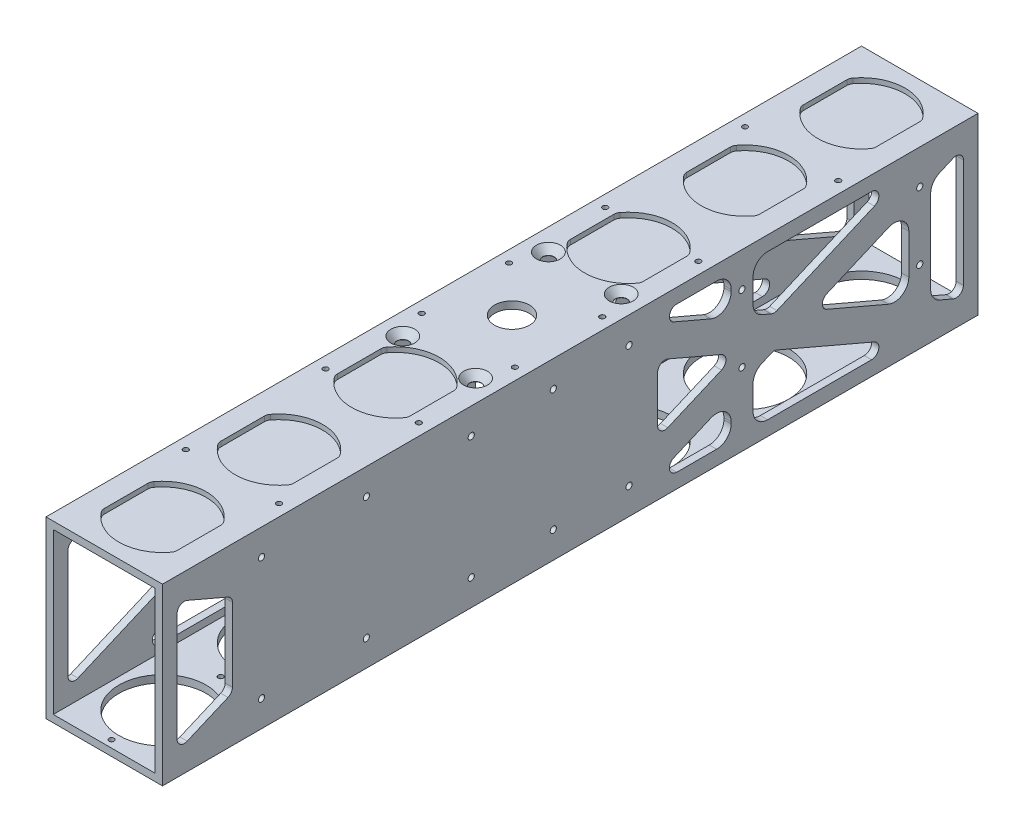
SolidWorks part; units mm, degrees
material "6061-T6 (SS)"
ref_plane "Front Plane" through (0, 0, 0) normal (0, 0, 1) x (1, 0, 0)
ref_plane "Top Plane" through (0, 0, 0) normal (0, 1, 0) x (1, 0, 0)
ref_plane "Right Plane" through (0, 0, 0) normal (1, 0, 0) x (0, 0, -1)
sketch "Sketch1" plane through (0, 0, 0) normal (0, 0, 1) x (1, 0, 0)
  line L0 (3.175, 3.175) -> (3.175, 73.025)
  line L1 (0, 0) -> (50.8, 0)
  line L2 (0, 0) -> (0, 76.2)
  line L3 (0, 76.2) -> (50.8, 76.2)
  line L4 (50.8, 0) -> (50.8, 76.2)
  line L5 (3.175, 73.025) -> (47.625, 73.025)
  line L6 (47.625, 3.175) -> (47.625, 73.025)
  line L7 (3.175, 3.175) -> (47.625, 3.175)
  dimension "D1" = 76.2
  dimension "D2" = 50.8
  dimension "D3" = 3.175
extrude "Boss-Extrude1" add sketch "Sketch1" along normal blind 355.6
sketch "Sketch2" plane through (50.8, 0, 0) normal (1, 0, 0) x (0, 0, -1)
  line L0 (-355.6, 76.2) -> (-177.8, 0) construction
  line L1 (-355.6, 0) -> (0, 0) construction
  line L2 (-177.8, 0) -> (-177.8, 76.2) construction
  line L3 (-355.6, 76.2) -> (0, 76.2) construction
  line L4 (-177.8, 76.2) -> (0, 0) construction
  line L5 (-355.6, 0) -> (-177.8, 76.2) construction
  line L6 (0, 76.2) -> (-177.8, 0) construction
  line L7 (-171.45, 61.755) -> (-171.45, 14.445)
  line L8 (-310.4456, 63.7567) -> (-267.9507, 45.5446)
  line L9 (-358.1014, 70.3634) -> (-180.3014, -5.8366) construction
  line L10 (-353.0986, 82.0366) -> (-175.2986, 5.8366) construction
  line L11 (-344.8243, 64.6733) -> (-289.6294, 41.0183)
  line L12 (-358.1014, 5.8366) -> (-180.3014, 82.0366) construction
  line L13 (-175.2986, 82.0366) -> (2.5014, 5.8366) construction
  line L14 (-353.0986, -5.8366) -> (-175.2986, 70.3634) construction
  line L15 (-184.15, 61.755) -> (-184.15, 14.445)
  line L16 (-45.1544, 63.7567) -> (-87.6493, 45.5446)
  line L17 (-10.7757, 64.6733) -> (-65.9706, 41.0183)
  line L18 (-132.6456, 63.7567) -> (-90.1507, 45.5446)
  line L19 (-167.0243, 64.6733) -> (-111.8294, 41.0183)
  line L20 (-6.35, 6.35) -> (-6.35, 69.85)
  line L21 (-6.35, 69.85) -> (-349.25, 69.85)
  line L22 (-349.25, 69.85) -> (-349.25, 6.35)
  line L23 (-349.25, 6.35) -> (-6.35, 6.35)
  line L24 (-6.35, 14.445) -> (-6.35, 61.755)
  line L25 (-224.2051, 69.85) -> (-309.1949, 69.85)
  line L26 (-349.25, 61.755) -> (-349.25, 14.445)
  line L27 (-309.1949, 6.35) -> (-224.2051, 6.35)
  line L28 (-344.8243, 11.5267) -> (-289.6294, 35.1817)
  line L29 (-310.4456, 12.4433) -> (-267.9507, 30.6554)
  line L30 (-265.4493, 45.5446) -> (-222.9544, 63.7567)
  line L31 (-243.7706, 41.0183) -> (-188.5757, 64.6733)
  line L32 (-180.3014, 70.3634) -> (-2.5014, -5.8366) construction
  line L33 (-265.4493, 30.6554) -> (-222.9544, 12.4433)
  line L34 (2.5014, 70.3634) -> (-175.2986, -5.8366) construction
  line L35 (-2.5014, 82.0366) -> (-180.3014, 5.8366) construction
  line L36 (-243.7706, 35.1817) -> (-188.5757, 11.5267)
  line L37 (-111.8294, 35.1817) -> (-167.0243, 11.5267)
  line L38 (-87.6493, 30.6554) -> (-45.1544, 12.4433)
  line L39 (-65.9706, 35.1817) -> (-10.7757, 11.5267)
  line L40 (-90.1507, 30.6554) -> (-132.6456, 12.4433)
  line L41 (-131.3949, 69.85) -> (-46.4051, 69.85)
  line L42 (-131.3949, 6.35) -> (-46.4051, 6.35)
  arc A0 (-65.9706, 35.1817) -> (-65.9706, 41.0183) centre (-64.7199, 38.1) cw
  arc A1 (-87.6493, 45.5446) -> (-90.1507, 45.5446) centre (-88.9, 48.4629) cw
  arc A2 (-167.0243, 11.5267) -> (-171.45, 14.445) centre (-168.275, 14.445) cw
  arc A3 (-171.45, 61.755) -> (-167.0243, 64.6733) centre (-168.275, 61.755) cw
  arc A4 (-224.2051, 6.35) -> (-222.9544, 12.4433) centre (-224.2051, 9.525) ccw
  arc A5 (-309.1949, 6.35) -> (-310.4456, 12.4433) centre (-309.1949, 9.525) cw
  arc A6 (-265.4493, 30.6554) -> (-267.9507, 30.6554) centre (-266.7, 27.7371) ccw
  arc A7 (-188.5757, 11.5267) -> (-184.15, 14.445) centre (-187.325, 14.445) ccw
  arc A8 (-184.15, 61.755) -> (-188.5757, 64.6733) centre (-187.325, 61.755) ccw
  arc A9 (-243.7706, 35.1817) -> (-243.7706, 41.0183) centre (-242.5199, 38.1) cw
  arc A10 (-222.9544, 63.7567) -> (-224.2051, 69.85) centre (-224.2051, 66.675) ccw
  arc A11 (-309.1949, 69.85) -> (-310.4456, 63.7567) centre (-309.1949, 66.675) ccw
  arc A12 (-265.4493, 45.5446) -> (-267.9507, 45.5446) centre (-266.7, 48.4629) cw
  arc A13 (-289.6294, 35.1817) -> (-289.6294, 41.0183) centre (-290.8801, 38.1) ccw
  arc A14 (-344.8243, 11.5267) -> (-349.25, 14.445) centre (-346.075, 14.445) cw
  arc A15 (-349.25, 61.755) -> (-344.8243, 64.6733) centre (-346.075, 61.755) cw
  arc A16 (-111.8294, 35.1817) -> (-111.8294, 41.0183) centre (-113.0801, 38.1) ccw
  arc A17 (-6.35, 61.755) -> (-10.7757, 64.6733) centre (-9.525, 61.755) ccw
  arc A18 (-6.35, 14.445) -> (-10.7757, 11.5267) centre (-9.525, 14.445) cw
  arc A19 (-45.1544, 12.4433) -> (-46.4051, 6.35) centre (-46.4051, 9.525) cw
  arc A20 (-131.3949, 6.35) -> (-132.6456, 12.4433) centre (-131.3949, 9.525) cw
  arc A21 (-87.6493, 30.6554) -> (-90.1507, 30.6554) centre (-88.9, 27.7371) ccw
  arc A22 (-45.1544, 63.7567) -> (-46.4051, 69.85) centre (-46.4051, 66.675) ccw
  arc A23 (-131.3949, 69.85) -> (-132.6456, 63.7567) centre (-131.3949, 66.675) ccw
  point P36 (-260.35, 0)
  point P37 (-260.35, 101.6)
  point P38 (-247.65, 0)
  point P39 (-247.65, 101.6)
  point P77 (-266.7, 31.1914)
  point P83 (-250.5799, 38.1)
  point P104 (-30.9367, 6.35)
  point P107 (-146.8633, 6.35)
  point P110 (-88.9, 31.1914)
  point P113 (-30.9367, 69.85)
  point P116 (-146.8633, 69.85)
  dimension "D13" = 3.175
  dimension "D14" = 3.175
  dimension "D11" = 6.35
  dimension "D12" = 6.35
  dimension "D2" = 6.35
  dimension "D3" = 6.35
  dimension "D4" = 6.35
  dimension "D5" = 6.35
  dimension "D6" = 6.35
  dimension "D7" = 6.35
  dimension "D8" = 6.35
  dimension "D9" = 6.35
  dimension "D10" = 6.35
extrude "Cut-Extrude2" cut sketch "Sketch2" against normal through all
hole_wizard "9/16 (0.5625) Diameter Hole1" positions "Sketch4" profile "Sketch5" hole size "9/16" standard "Ansi Inch"
sketch "Sketch4" plane through (0, 76.2, 0) normal (0, 1, 0) x (-1, 0, 0)
  line L4 (-50.8, 355.6) -> (-50.8, 0) construction
  line L5 (-50.8, 177.8) -> (0, 177.8) construction
  line L6 (0, 355.6) -> (0, 0) construction
  point P0 (-25.4, 177.8)
sketch "Sketch5" plane through (25.4, 76.2, 177.8) normal (1, 0, 0) x (0, 0, 1)
  line L0 (0, 0) -> (0, 3.175)
  line L1 (0, 3.175) -> (7.62, 3.175)
  line L2 (7.62, 3.175) -> (7.62, 0)
  line L5 (7.62, 0) -> (0, 0)
  line L11 (0, -6.35) -> (0, 107.95) construction
  dimension "Thru Hole Dia." = 15.24
  dimension "Thru Hole Depth" = 3.175
sketch "Sketch6" plane through (0, 76.2, 0) normal (0, 1, 0) x (1, 0, 0)
  line L0 (50.8, 0) -> (0, 0) construction
  line L2 (50.8, -355.6) -> (50.8, 0) construction
  circle A0 centre (25.4, -25.4) radius 19.05
  circle A1 centre (25.4, -76.2) radius 19.05
  circle A2 centre (25.4, -127) radius 19.05
  circle A3 centre (25.4, -177.8) radius 19.05 [skipped]
  circle A4 centre (25.4, -228.6) radius 19.05
  circle A5 centre (25.4, -279.4) radius 19.05
  circle A6 centre (25.4, -330.2) radius 19.05
  dimension "D1" = 38.1
  dimension "D2" = 25.4
  dimension "D3" = 25.4
  dimension "D5" = 7
extrude "Cut-Extrude3" cut sketch "Sketch6" against normal through all
hole_wizard "CSK for #10 Flat Head Socket Cap Screw1" positions "Sketch8" profile "Sketch7" countersink size "#10" standard "Ansi Inch" end condition up to next
sketch "Sketch8" plane through (0, 76.2, 0) normal (0, 1, 0) x (-1, 0, 0)
  line L0 (-50.8, 177.8) -> (0, 177.8) construction
  line L1 (-50.8, 355.6) -> (-50.8, 0) construction
  line L2 (0, 355.6) -> (0, 0) construction
  line L4 (-25.4, 0) -> (-25.4, 355.6) construction
  line L5 (-50.8, 0) -> (0, 0) construction
  line L6 (-50.8, 355.6) -> (0, 355.6) construction
  point P0 (-41.275, 146.05)
  point P1 (-9.525, 146.05)
  point P3 (-41.275, 209.55)
  point P5 (-9.525, 209.55)
  dimension "D1" = 31.75
  dimension "D2" = 15.875
  dimension "D3" = 15.875
  dimension "D4" = 31.75
sketch "Sketch7" plane through (41.275, 76.2, 146.05) normal (1, 0, 0) x (0, 0, 1)
  line L0 (0, 0) -> (0, 3.175)
  line L1 (0, 3.175) -> (2.5527, 3.175)
  line L2 (2.5527, 3.175) -> (2.5527, 3.068)
  line L3 (2.5527, 3.068) -> (5.2197, 0)
  line L5 (5.2197, 0) -> (0, 0)
  line L6 (-2.5527, 3.068) -> (-5.2197, 0) construction
  line L11 (0, -6.35) -> (0, 107.95) construction
  dimension "Thru Hole Dia." = 5.1054
  dimension "Thru Hole Depth" = 3.175
  dimension "Near C'Sink Dia." = 10.4394
  dimension "Near C'Sink Angle" = 82
sketch "Sketch9" plane through (0, 0, 0) normal (0, -1, 0) x (1, 0, 0)
  line L0 (0, 355.6) -> (0, 0) construction
  circle A0 centre (25.4, 177.8) radius 19.05
  circle A1 centre (25.4, 127) radius 19.05 construction
  dimension "D1" = 38.1
  dimension "D2" = 25.4
  dimension "D3" = 50.8
extrude "Cut-Extrude4" cut sketch "Sketch9" against normal up to next
sketch "Sketch10" plane through (50.8, 0, 0) normal (1, 0, 0) x (0, 0, -1)
  line L0 (-266.7, 64.77) -> (-266.7, 11.43) construction
  line L1 (-312.42, 64.77) -> (-220.98, 64.77) construction
  line L2 (-312.42, 64.77) -> (-312.42, 11.43) construction
  line L3 (-312.42, 11.43) -> (-220.98, 11.43) construction
  line L4 (-220.98, 64.77) -> (-220.98, 11.43) construction
  line L5 (-355.6, 38.1) -> (0, 38.1) construction
  line L6 (-355.6, 0) -> (-355.6, 76.2) construction
  line L7 (0, 0) -> (0, 76.2) construction
  line L9 (-325.12, 7.62) -> (-208.28, 7.62) construction
  line L10 (-325.12, 19.9715) -> (-325.12, 56.2285) construction
  line L11 (-325.12, 68.58) -> (-208.28, 68.58) construction
  line L12 (-171.45, 4.1872) -> (-171.45, 9.63) construction
  line L13 (-325.12, 7.62) -> (-208.28, 68.58) construction
  line L14 (-325.12, 68.58) -> (-208.28, 7.62) construction
  line L15 (-325.12, 56.2285) -> (-325.12, 19.9715)
  line L18 (-171.45, 9.63) -> (-171.45, 4.1872)
  line L20 (-188.5757, 64.6733) -> (-243.7706, 41.0183) construction
  line L22 (-243.7706, 35.1817) -> (-188.5757, 11.5267) construction
  line L24 (-167.0243, 73.9096) -> (-243.7706, 41.0183)
  line L25 (-243.7706, 35.1817) -> (-171.45, 4.1872)
  line L26 (-289.6294, 41.0183) -> (-344.8243, 64.6733) construction
  line L27 (-344.8243, 11.5267) -> (-289.6294, 35.1817) construction
  line L28 (-289.6294, 41.0183) -> (-325.12, 56.2285)
  line L29 (-325.12, 19.9715) -> (-289.6294, 35.1817)
  line L30 (-355.6, 76.2) -> (0, 76.2) construction
  line L31 (-310.4456, 63.7567) -> (-267.9507, 45.5446) construction
  line L32 (-224.2051, 69.85) -> (-309.1949, 69.85) construction
  line L33 (-265.4493, 45.5446) -> (-222.9544, 63.7567) construction
  line L34 (-222.9544, 12.4433) -> (-265.4493, 30.6554) construction
  line L35 (-267.9507, 30.6554) -> (-310.4456, 12.4433) construction
  line L36 (-309.1949, 6.35) -> (-224.2051, 6.35) construction
  line L37 (-310.4456, 63.7567) -> (-267.9507, 45.5446)
  line L38 (-224.2051, 69.85) -> (-309.1949, 69.85)
  line L39 (-265.4493, 45.5446) -> (-222.9544, 63.7567)
  line L40 (-222.9544, 12.4433) -> (-265.4493, 30.6554)
  line L41 (-267.9507, 30.6554) -> (-310.4456, 12.4433)
  line L42 (-309.1949, 6.35) -> (-224.2051, 6.35)
  line L45 (-139.7, 52.9628) -> (-139.7, 23.2372)
  line L46 (-111.8294, 41.0183) -> (-167.0243, 64.6733) construction
  line L47 (-167.0243, 11.5267) -> (-111.8294, 35.1817) construction
  line L48 (-171.45, 61.755) -> (-171.45, 14.445) construction
  line L49 (-139.7, 52.9628) -> (-167.0243, 64.6733)
  line L50 (-171.45, 9.63) -> (-139.7, 23.2372)
  line L51 (-167.0243, 64.6733) -> (-167.0243, 73.9096)
  arc A0 (-243.7706, 41.0183) -> (-243.7706, 35.1817) centre (-242.5199, 38.1) ccw construction
  arc A2 (-243.7706, 41.0183) -> (-243.7706, 35.1817) centre (-242.5199, 38.1) ccw
  arc A4 (-289.6294, 35.1817) -> (-289.6294, 41.0183) centre (-290.8801, 38.1) ccw construction
  arc A5 (-289.6294, 35.1817) -> (-289.6294, 41.0183) centre (-290.8801, 38.1) ccw
  arc A6 (-309.1949, 69.85) -> (-310.4456, 63.7567) centre (-309.1949, 66.675) ccw construction
  arc A7 (-222.9544, 63.7567) -> (-224.2051, 69.85) centre (-224.2051, 66.675) ccw construction
  arc A8 (-267.9507, 45.5446) -> (-265.4493, 45.5446) centre (-266.7, 48.4629) ccw construction
  arc A9 (-265.4493, 30.6554) -> (-267.9507, 30.6554) centre (-266.7, 27.7371) ccw construction
  arc A10 (-310.4456, 12.4433) -> (-309.1949, 6.35) centre (-309.1949, 9.525) ccw construction
  arc A11 (-224.2051, 6.35) -> (-222.9544, 12.4433) centre (-224.2051, 9.525) ccw construction
  arc A12 (-309.1949, 69.85) -> (-310.4456, 63.7567) centre (-309.1949, 66.675) ccw
  arc A13 (-222.9544, 63.7567) -> (-224.2051, 69.85) centre (-224.2051, 66.675) ccw
  arc A14 (-267.9507, 45.5446) -> (-265.4493, 45.5446) centre (-266.7, 48.4629) ccw
  arc A15 (-265.4493, 30.6554) -> (-267.9507, 30.6554) centre (-266.7, 27.7371) ccw
  arc A16 (-310.4456, 12.4433) -> (-309.1949, 6.35) centre (-309.1949, 9.525) ccw
  arc A17 (-224.2051, 6.35) -> (-222.9544, 12.4433) centre (-224.2051, 9.525) ccw
  point P13 (-266.7, 38.1)
  dimension "D1" = 53.34
  dimension "D2" = 215.9
  dimension "D3" = 116.84
  dimension "D4" = 60.96
  dimension "D5" = 91.44
  dimension "D7" = 30.48
  dimension "D8" = 7.62
  dimension "D9" = 3.81
  dimension "D10" = 12.7
extrude "Boss-Extrude2" add sketch "Sketch10" against normal up to surface (3.175 mm away) up to face at (47.625, 16.3557, 88.9)
fillet "Fillet1" radius 3.175 4 edges at (49.2125, 19.9715, 325.12) (49.2125, 56.2285, 325.12) (49.2125, 23.2372, 139.7) (49.2125, 52.9628, 139.7)
hole_wizard "#6-32 Tapped Hole1" positions "Sketch12" profile "Sketch11" tap size "#6-32" standard "Ansi Inch"
sketch "Sketch12" plane through (50.8, 0, 0) normal (1, 0, 0) x (0, 0, -1)
  point P0 (-312.42, 64.77)
  point P1 (-266.7, 64.77)
  point P4 (-220.98, 64.77)
  point P7 (-220.98, 11.43)
  point P10 (-266.7, 11.43)
  point P13 (-312.42, 11.43)
sketch "Sketch11" plane through (50.8, 64.77, 312.42) normal (0, 1, 0) x (0, 0, -1)
  line L0 (0, 0) -> (0, 3.175)
  line L1 (0, 3.175) -> (1.3525, 3.175)
  line L2 (1.3525, 3.175) -> (1.3525, 0)
  line L5 (1.3525, 0) -> (0, 0)
  line L11 (0, -6.35) -> (0, 107.95) construction
  dimension "Thru Tap Drill Dia." = 2.7051
  dimension "Thru Tap Drill Depth" = 3.175
cosmetic thread "Hole Thread1"
cosmetic thread "Hole Thread2"
cosmetic thread "Hole Thread3"
cosmetic thread "Hole Thread4"
cosmetic thread "Hole Thread5"
cosmetic thread "Hole Thread6"
sketch "Sketch13" plane through (50.8, 0, 0) normal (1, 0, 0) x (0, 0, -1)
  line L0 (-355.6, 38.1) -> (0, 38.1) construction
  line L1 (-355.6, 0) -> (-355.6, 76.2) construction
  line L2 (0, 0) -> (0, 76.2) construction
  line L4 (-197.6628, 8.1026) -> (-139.7, 8.1026) construction
  line L5 (-197.6628, 8.1026) -> (-197.6628, 68.0974) construction
  line L6 (-197.6628, 68.0974) -> (-139.7, 68.0974) construction
  line L7 (-139.7, 8.1026) -> (-139.7, 68.0974) construction
  line L8 (-197.6628, 8.1026) -> (-139.7, 68.0974) construction
  line L9 (-197.6628, 68.0974) -> (-139.7, 8.1026) construction
  line L10 (-185.1914, 11.5697) -> (-152.1714, 11.5697) construction
  line L11 (-185.1914, 11.5697) -> (-185.1914, 64.6303) construction
  line L12 (-185.1914, 64.6303) -> (-152.1714, 64.6303) construction
  line L13 (-152.1714, 11.5697) -> (-152.1714, 64.6303) construction
  line L14 (-185.1914, 11.5697) -> (-152.1714, 64.6303) construction
  line L15 (-185.1914, 64.6303) -> (-152.1714, 11.5697) construction
  point P6 (-168.6814, 38.1)
  point P11 (-168.6814, 38.1)
  dimension "D1" = 139.7
  dimension "D2" = 59.9948
  dimension "D3" = 57.9628
  dimension "D4" = 53.0606
  dimension "D5" = 33.02
hole_wizard "#6-32 Tapped Hole2" positions "Sketch15" profile "Sketch14" tap size "#6-32" standard "Ansi Inch"
sketch "Sketch15" plane through (50.8, 0, 0) normal (1, 0, 0) x (0, 0, -1)
  point P0 (-152.1714, 64.6303)
  point P1 (-185.1914, 64.6303)
  point P4 (-185.1914, 11.5697)
  point P7 (-152.1714, 11.5697)
cosmetic thread "Hole Thread7"
cosmetic thread "Hole Thread8"
cosmetic thread "Hole Thread9"
cosmetic thread "Hole Thread10"
sketch "Sketch14" plane through (50.8, 64.6303, 152.1714) normal (0, 1, 0) x (0, 0, -1)
  line L0 (0, 0) -> (0, 3.175)
  line L1 (0, 3.175) -> (1.3525, 3.175)
  line L2 (1.3525, 3.175) -> (1.3525, 0)
  line L5 (1.3525, 0) -> (0, 0)
  line L11 (0, -6.35) -> (0, 107.95) construction
  dimension "Thru Tap Drill Dia." = 2.7051
  dimension "Thru Tap Drill Depth" = 3.175
sketch "Sketch20" plane through (50.8, 0, 0) normal (1, 0, 0) x (0, 0, -1)
  line L0 (-102.87, 76.2) -> (-102.87, 0) construction
  line L1 (-355.6, 76.2) -> (0, 76.2) construction
  line L2 (-355.6, 0) -> (0, 0) construction
  line L3 (-25.4, 76.2) -> (-25.4, 0) construction
  line L4 (0, 0) -> (0, 76.2) construction
  line L5 (-107.6325, 69.85) -> (-107.6325, 53.0368)
  line L6 (-30.1625, 56.3646) -> (-30.1625, 19.8354)
  line L7 (-98.1075, 69.85) -> (-98.1075, 48.9547)
  line L8 (-20.6375, 60.4468) -> (-20.6375, 15.7532)
  line L9 (-46.4051, 69.85) -> (-131.3949, 69.85) construction
  line L10 (-132.6456, 63.7567) -> (-90.1507, 45.5446) construction
  line L11 (-90.1507, 30.6554) -> (-132.6456, 12.4433) construction
  line L12 (-131.3949, 6.35) -> (-46.4051, 6.35) construction
  line L13 (-10.7757, 64.6733) -> (-65.9706, 41.0183) construction
  line L14 (-65.9706, 35.1817) -> (-10.7757, 11.5267) construction
  line L15 (-98.1075, 69.85) -> (-107.6325, 69.85)
  line L16 (-107.6325, 53.0368) -> (-98.1075, 48.9547)
  line L17 (-98.1075, 27.2453) -> (-107.6325, 23.1632)
  line L18 (-107.6325, 6.35) -> (-98.1075, 6.35)
  line L19 (-20.6375, 60.4468) -> (-30.1625, 56.3646)
  line L20 (-30.1625, 19.8354) -> (-20.6375, 15.7532)
  line L21 (-98.1075, 76.2) -> (-98.1075, 0) construction
  line L22 (-107.6325, 76.2) -> (-107.6325, 0) construction
  line L23 (-107.6325, 23.1632) -> (-107.6325, 6.35)
  line L24 (-98.1075, 27.2453) -> (-98.1075, 6.35)
  line L25 (-30.1625, 76.2) -> (-30.1625, 0) construction
  line L26 (-20.6375, 76.2) -> (-20.6375, 0) construction
  dimension "D1" = 77.47
  dimension "D2" = 25.4
  dimension "D3" = 4.7625
  dimension "D4" = 4.7625
extrude "Boss-Extrude7" add sketch "Sketch20" against normal up to surface (3.175 mm away) up to face at (47.625, 64.6303, 153.5239)
fillet "Fillet6" radius 6.35 12 edges at (49.2125, 60.4468, 20.6375) (49.2125, 15.7532, 20.6375) (49.2125, 19.8354, 30.1625) (49.2125, 56.3646, 30.1625) (49.2125, 6.35, 98.1075) (49.2125, 6.35, 107.6325) (49.2125, 23.1632, 107.6325) (49.2125, 27.2453, 98.1075) (49.2125, 69.85, 98.1075) (49.2125, 48.9547, 98.1075) (49.2125, 69.85, 107.6325) (49.2125, 53.0368, 107.6325)
hole_wizard "#6-32 Tapped Hole3" positions "Sketch24" profile "Sketch23" tap size "#6-32" standard "Ansi Inch"
sketch "Sketch24" plane through (50.8, 0, 0) normal (1, 0, 0) x (0, 0, -1)
  line L0 (0, 38.1) -> (-164.5823, 38.1) construction
  line L1 (0, 0) -> (0, 76.2) construction
  point P0 (-102.9, 61.1)
  point P1 (-25.4, 61.1)
  point P3 (-25.4, 31.75)
  point P5 (-102.9, 31.75)
  dimension "D1" = 77.5
  dimension "D2" = 6.35
  dimension "D3" = 29.35
  dimension "D4" = 25.4
sketch "Sketch23" plane through (50.8, 61.1, 102.9) normal (0, 1, 0) x (0, 0, -1)
  line L0 (0, 0) -> (0, 10.2107)
  line L1 (0, 10.2107) -> (1.3525, 9.398)
  line L2 (1.3525, 9.398) -> (1.3525, 0)
  line L5 (1.3525, 0) -> (0, 0)
  line L10 (0, 10.2107) -> (-1.3525, 9.398) construction
  line L11 (0, -6.35) -> (0, 107.95) construction
  dimension "Tap Drill Dia." = 2.7051
  dimension "Tap Drill Depth" = 9.398
  dimension "Drill Angle" = 118
cosmetic thread "Hole Thread11"
cosmetic thread "Hole Thread12"
cosmetic thread "Hole Thread13"
cosmetic thread "Hole Thread14"
hole_wizard "#4-40 Tapped Hole1" positions "Sketch26" profile "Sketch27" tap size "#4-40" standard "Ansi Inch"
sketch "Sketch26" plane through (0, 0, 0) normal (0, -1, 0) x (1, 0, 0)
  line L0 (0, 355.6) -> (50.8, 355.6) construction
  line L1 (25.4, 311.15) -> (25.4, 298.45) construction
  line L3 (0, 0) -> (50.8, 0) construction
  circle A0 centre (25.4, 330.2) radius 19.05 construction
  circle A1 centre (25.4, 279.4) radius 19.05 construction
  point P0 (25.4, 304.8)
  point P1 (25.4, 352.425)
  point P26 (25.4, 254)
  point P27 (25.4, 203.2)
  point P28 (25.4, 152.4)
  point P29 (25.4, 101.6)
  point P30 (25.4, 50.8)
  point P31 (25.4, 3.175)
  dimension "D1" = 3.175
  dimension "D3" = 3.175
  dimension "D4" = 50.8
  dimension "D2" = 6
sketch "Sketch27" plane through (25.4, 0, 304.8) normal (1, 0, 0) x (0, 0, -1)
  line L0 (0, 0) -> (0, 3.175)
  line L1 (0, 3.175) -> (1.1303, 3.175)
  line L2 (1.1303, 3.175) -> (1.1303, 0)
  line L5 (1.1303, 0) -> (0, 0)
  line L11 (0, -6.35) -> (0, 107.95) construction
  dimension "Thread Major Dia." = 2.2606
  dimension "Thru Tap Drill Depth" = 3.175
sketch "Sketch29" plane through (0, 76.2, 0) normal (0, 1, 0) x (1, 0, 0)
  line L0 (9.525, -14.8697) -> (9.525, -35.9303)
  line L3 (41.275, -14.8697) -> (41.275, -35.9303)
  line L5 (0, -355.6) -> (0, 0) construction
  line L6 (50.8, -355.6) -> (50.8, 0) construction
  line L7 (41.275, -116.4697) -> (41.275, -137.5303)
  line L8 (9.525, -116.4697) -> (9.525, -137.5303)
  line L9 (41.275, -65.6697) -> (41.275, -86.7303)
  line L10 (9.525, -65.6697) -> (9.525, -86.7303)
  line L11 (41.275, -218.0697) -> (41.275, -239.1303)
  line L12 (9.525, -218.0697) -> (9.525, -239.1303)
  line L13 (41.275, -268.8697) -> (41.275, -289.9303)
  line L14 (9.525, -268.8697) -> (9.525, -289.9303)
  line L15 (41.275, -319.6697) -> (41.275, -340.7303)
  line L16 (9.525, -319.6697) -> (9.525, -340.7303)
  circle A0 centre (25.4, -25.4) radius 19.05 construction
  circle A1 centre (25.4, -76.2) radius 19.05 construction
  circle A2 centre (25.4, -127) radius 19.05 construction
  circle A3 centre (25.4, -228.6) radius 19.05 construction
  circle A4 centre (25.4, -279.4) radius 19.05 construction
  circle A5 centre (25.4, -330.2) radius 19.05 construction
  arc A6 (9.525, -14.8697) -> (9.525, -35.9303) centre (25.4, -25.4) ccw
  arc A7 (9.525, -65.6697) -> (9.525, -86.7303) centre (25.4, -76.2) ccw
  arc A8 (9.525, -116.4697) -> (9.525, -137.5303) centre (25.4, -127) ccw
  arc A9 (9.525, -218.0697) -> (9.525, -239.1303) centre (25.4, -228.6) ccw
  arc A10 (9.525, -268.8697) -> (9.525, -289.9303) centre (25.4, -279.4) ccw
  arc A11 (9.525, -319.6697) -> (9.525, -340.7303) centre (25.4, -330.2) ccw
  arc A12 (41.275, -35.9303) -> (41.275, -14.8697) centre (25.4, -25.4) ccw
  arc A13 (41.275, -86.7303) -> (41.275, -65.6697) centre (25.4, -76.2) ccw
  arc A14 (41.275, -137.5303) -> (41.275, -116.4697) centre (25.4, -127) ccw
  arc A15 (41.275, -239.1303) -> (41.275, -218.0697) centre (25.4, -228.6) ccw
  arc A16 (41.275, -289.9303) -> (41.275, -268.8697) centre (25.4, -279.4) ccw
  arc A17 (41.275, -340.7303) -> (41.275, -319.6697) centre (25.4, -330.2) ccw
  dimension "D1" = 9.525
  dimension "D2" = 9.525
extrude "Boss-Extrude8" add sketch "Sketch29" against normal up to surface (3.175 mm away) up to face at (41.275, 73.025, 143.4973)
sketch "Sketch30" plane through (0, 73.025, 0) normal (0, -1, 0) x (1, 0, 0)
  line L2 (9.525, 340.7303) -> (9.525, 319.6697)
  line L3 (41.275, 319.6697) -> (41.275, 340.7303)
  line L4 (9.525, 340.7303) -> (9.525, 319.6697)
  line L5 (41.275, 319.6697) -> (41.275, 340.7303)
  line L6 (9.525, 289.9303) -> (9.525, 268.8697)
  line L7 (41.275, 268.8697) -> (41.275, 289.9303)
  line L8 (9.525, 289.9303) -> (9.525, 268.8697)
  line L9 (41.275, 268.8697) -> (41.275, 289.9303)
  line L10 (41.275, 218.0697) -> (41.275, 239.1303)
  line L11 (9.525, 239.1303) -> (9.525, 218.0697)
  line L12 (41.275, 218.0697) -> (41.275, 239.1303)
  line L13 (9.525, 239.1303) -> (9.525, 218.0697)
  line L14 (9.525, 137.5303) -> (9.525, 116.4697)
  line L15 (41.275, 116.4697) -> (41.275, 137.5303)
  line L16 (9.525, 137.5303) -> (9.525, 116.4697)
  line L17 (41.275, 116.4697) -> (41.275, 137.5303)
  line L18 (9.525, 86.7303) -> (9.525, 65.6697)
  line L19 (41.275, 65.6697) -> (41.275, 86.7303)
  line L20 (9.525, 86.7303) -> (9.525, 65.6697)
  line L21 (41.275, 65.6697) -> (41.275, 86.7303)
  line L22 (41.275, 14.8697) -> (41.275, 35.9303)
  line L23 (9.525, 35.9303) -> (9.525, 14.8697)
  line L24 (41.275, 14.8697) -> (41.275, 35.9303)
  line L25 (9.525, 35.9303) -> (9.525, 14.8697)
  arc A2 (9.525, 319.6697) -> (41.275, 319.6697) centre (25.4, 330.2) ccw
  arc A3 (41.275, 340.7303) -> (9.525, 340.7303) centre (25.4, 330.2) ccw
  arc A4 (9.525, 319.6697) -> (41.275, 319.6697) centre (25.4, 330.2) ccw
  arc A5 (41.275, 340.7303) -> (9.525, 340.7303) centre (25.4, 330.2) ccw
  arc A6 (9.525, 268.8697) -> (41.275, 268.8697) centre (25.4, 279.4) ccw
  arc A7 (41.275, 289.9303) -> (9.525, 289.9303) centre (25.4, 279.4) ccw
  arc A8 (9.525, 268.8697) -> (41.275, 268.8697) centre (25.4, 279.4) ccw
  arc A9 (41.275, 289.9303) -> (9.525, 289.9303) centre (25.4, 279.4) ccw
  arc A10 (41.275, 239.1303) -> (9.525, 239.1303) centre (25.4, 228.6) ccw
  arc A11 (9.525, 218.0697) -> (41.275, 218.0697) centre (25.4, 228.6) ccw
  arc A12 (41.275, 239.1303) -> (9.525, 239.1303) centre (25.4, 228.6) ccw
  arc A13 (9.525, 218.0697) -> (41.275, 218.0697) centre (25.4, 228.6) ccw
  arc A14 (9.525, 116.4697) -> (41.275, 116.4697) centre (25.4, 127) ccw
  arc A15 (41.275, 137.5303) -> (9.525, 137.5303) centre (25.4, 127) ccw
  arc A16 (9.525, 116.4697) -> (41.275, 116.4697) centre (25.4, 127) ccw
  arc A17 (41.275, 137.5303) -> (9.525, 137.5303) centre (25.4, 127) ccw
  arc A18 (9.525, 65.6697) -> (41.275, 65.6697) centre (25.4, 76.2) ccw
  arc A19 (41.275, 86.7303) -> (9.525, 86.7303) centre (25.4, 76.2) ccw
  arc A20 (9.525, 65.6697) -> (41.275, 65.6697) centre (25.4, 76.2) ccw
  arc A21 (41.275, 86.7303) -> (9.525, 86.7303) centre (25.4, 76.2) ccw
  arc A22 (41.275, 35.9303) -> (9.525, 35.9303) centre (25.4, 25.4) ccw
  arc A23 (9.525, 14.8697) -> (41.275, 14.8697) centre (25.4, 25.4) ccw
  arc A24 (41.275, 35.9303) -> (9.525, 35.9303) centre (25.4, 25.4) ccw
  arc A25 (9.525, 14.8697) -> (41.275, 14.8697) centre (25.4, 25.4) ccw
  dimension "D1" = 0
  dimension "D2" = 0
  dimension "D3" = 0
  dimension "D4" = 0
  dimension "D5" = 0
  dimension "D6" = 0
extrude "Boss-Extrude9" add sketch "Sketch30" against normal blind 1.016
fillet "Fillet7" radius 3.175 24 edges at (9.525, 75.1205, 340.7303) (9.525, 75.1205, 319.6697) (41.275, 75.1205, 319.6697) (41.275, 75.1205, 340.7303) (41.275, 75.1205, 268.8697) (41.275, 75.1205, 289.9303) (9.525, 75.1205, 289.9303) (9.525, 75.1205, 268.8697) (41.275, 75.1205, 218.0697) (41.275, 75.1205, 239.1303) (9.525, 75.1205, 239.1303) (9.525, 75.1205, 218.0697) (41.275, 75.1205, 116.4697) (41.275, 75.1205, 137.5303) (9.525, 75.1205, 137.5303) (9.525, 75.1205, 116.4697) (9.525, 75.1205, 86.7303) (9.525, 75.1205, 65.6697) (41.275, 75.1205, 65.6697) (41.275, 75.1205, 86.7303) (9.525, 75.1205, 35.9303) (9.525, 75.1205, 14.8697) (41.275, 75.1205, 14.8697) (41.275, 75.1205, 35.9303)
hole_wizard "#4-40 Tapped Hole2" positions "Sketch35" profile "Sketch36" tap size "#4-40" standard "Ansi Inch"
sketch "Sketch35" plane through (0, 76.2, 0) normal (0, 1, 0) x (-1, 0, 0)
  line L0 (-50.8, 355.6) -> (-50.8, 0) construction
  line L1 (-50.8, 355.6) -> (0, 355.6) construction
  circle A0 centre (-25.4, 177.8) radius 7.62 construction
  point P0 (-45.72, 299.72)
  point P13 (-45.72, 238.76)
  point P15 (-45.72, 116.84)
  point P16 (-45.72, 55.88)
  point P17 (-45.72, 158.75)
  point P19 (-45.72, 196.85)
  point P21 (-45.72, 177.8) [skipped]
  dimension "D6" = 19.05
  dimension "D1" = 5.08
  dimension "D2" = 55.88
  dimension "D4" = 60.96
  dimension "D5" = 38.1
  dimension "D3" = 5
sketch "Sketch36" plane through (45.72, 76.2, 299.72) normal (1, 0, 0) x (0, 0, 1)
  line L0 (0, 0) -> (0, 76.2)
  line L1 (0, 76.2) -> (1.1303, 76.2)
  line L2 (1.1303, 76.2) -> (1.1303, 0)
  line L5 (1.1303, 0) -> (0, 0)
  line L11 (0, -6.35) -> (0, 107.95) construction
  dimension "Thread Major Dia." = 2.2606
  dimension "Thru Tap Drill Depth" = 76.2
ref_plane "Plane1" through (25.4, 0, 0) normal (1, 0, 0) x (0, 0, -1)
mirror "Mirror1" about plane through (25.4, 0, 0) normal (1, 0, 0) of "#4-40 Tapped Hole2"
